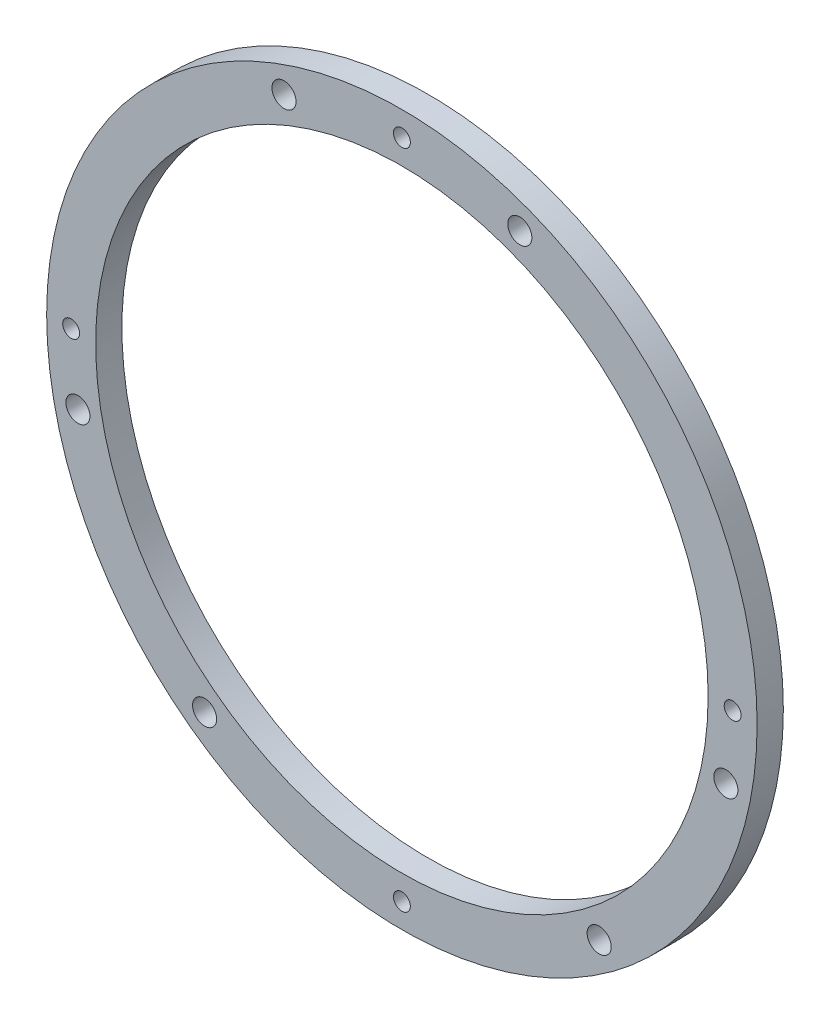
SolidWorks part; units mm, degrees
material "Acrylic (Medium-high impact)"
ref_plane "Front Plane" through (0, 0, 0) normal (0, 0, 1) x (1, 0, 0)
ref_plane "Top Plane" through (0, 0, 0) normal (0, 1, 0) x (1, 0, 0)
ref_plane "Right Plane" through (0, 0, 0) normal (1, 0, 0) x (0, 0, -1)
sketch "Sketch2" plane through (0, 0, -69.215) normal (0, 0, 1) x (1, 0, 0)
  line L0 (0, 68.58) -> (0, 0) construction
  line L1 (-57.8398, -36.848) -> (0, 0) construction
  line L2 (0, 0) -> (57.8398, -36.848) construction
  line L3 (0, 0) -> (0, -68.58) construction
  line L4 (-24.45, 64.0735) -> (24.45, 64.0735) construction
  line L5 (-67.176, -13.8058) -> (-40.9021, -55.0476) construction
  line L6 (40.9021, -55.0476) -> (67.176, -13.8058) construction
  circle A0 centre (0, 0) radius 74.93 construction
  circle A1 centre (0, 0) radius 63.5 construction
  circle A2 centre (0, -68.58) radius 1.25 construction
  circle A3 centre (68.58, 0) radius 1.25 construction
  circle A4 centre (0, 68.58) radius 1.25 construction
  circle A5 centre (-68.58, 0) radius 1.25 construction
  circle A6 centre (0, 0) radius 74.93 construction
  circle A7 centre (0, 0) radius 63.5
  circle A8 centre (0, -68.58) radius 1.25 construction
  circle A9 centre (68.58, 0) radius 1.25 construction
  circle A10 centre (0, 68.58) radius 1.25 construction
  circle A11 centre (-68.58, 0) radius 1.25 construction
  circle A12 centre (-68.58, 0) radius 1.75
  circle A13 centre (0, 68.58) radius 1.75
  circle A14 centre (68.58, 0) radius 1.75
  circle A15 centre (0, -68.58) radius 1.75
  circle A16 centre (0, 68.58) radius 5.08 construction
  circle A17 centre (0, 0) radius 73.66
  circle A18 centre (0, 0) radius 68.58 construction
  circle A19 centre (-24.45, 64.0735) radius 2.5
  circle A20 centre (24.45, 64.0735) radius 2.5
  circle A21 centre (-67.176, -13.8058) radius 2.5
  circle A22 centre (-40.9021, -55.0476) radius 2.5
  circle A23 centre (40.9021, -55.0476) radius 2.5
  circle A24 centre (67.176, -13.8058) radius 2.5
  dimension "D1" = 3.5
  dimension "D2" = 5
  dimension "D3" = 50
  dimension "D4" = 57.5
extrude "Boss-Extrude1" add sketch "Sketch2" along normal blind 5.4356
